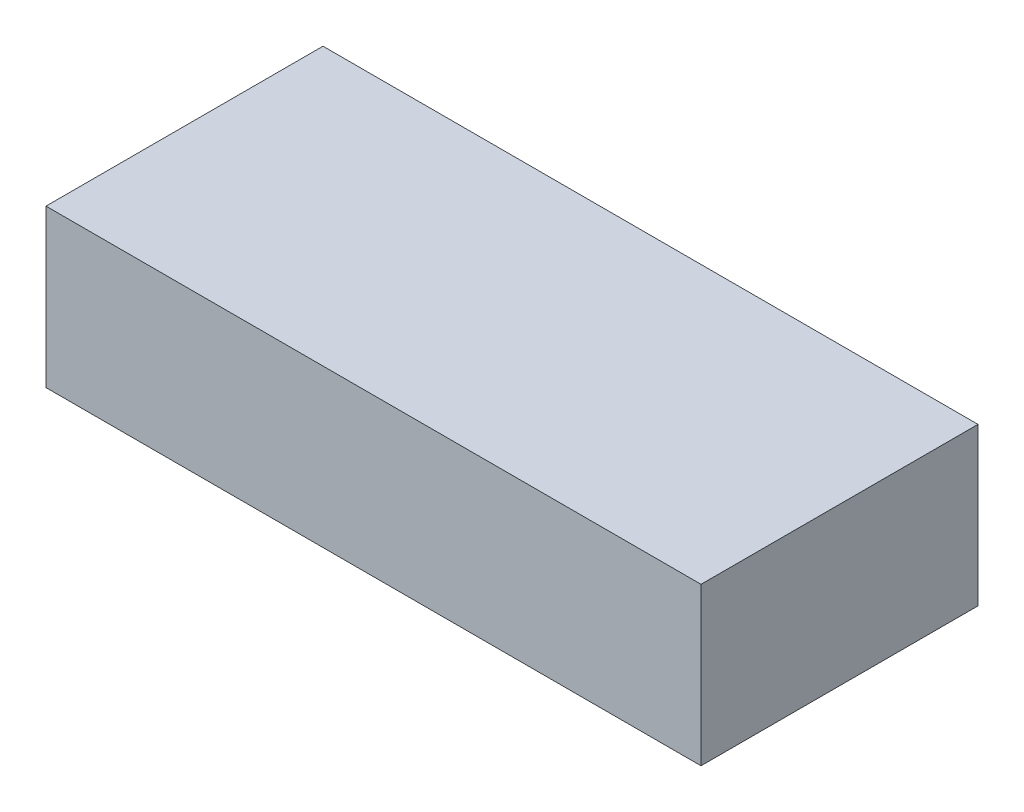
SolidWorks part; units mm, degrees
ref_plane "Front Plane" through (0, 0, 0) normal (0, 0, 1) x (1, 0, 0)
ref_plane "Top Plane" through (0, 0, 0) normal (0, 1, 0) x (1, 0, 0)
ref_plane "Right Plane" through (0, 0, 0) normal (1, 0, 0) x (0, 0, -1)
sketch "Sketch1" plane through (0, 0, 0) normal (0, 1, 0) x (1, 0, 0)
  line L1 (437.5, 0) -> (-437.5, 0)
  line L2 (437.5, 0) -> (437.5, 370)
  line L3 (437.5, 370) -> (-437.5, 370)
  line L4 (-437.5, 0) -> (-437.5, 370)
  point P4 (0, 0)
  point P6 (0, 370)
  dimension "D1" = 875
  dimension "D2" = 370
extrude "Boss-Extrude1" add sketch "Sketch1" against normal blind 210
